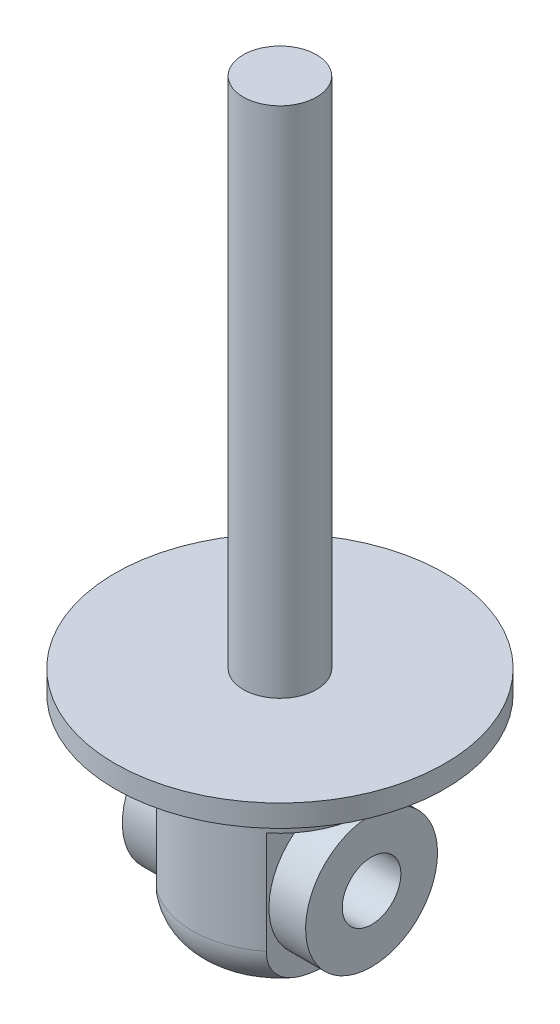
SolidWorks part; units mm, degrees
ref_plane "Plano frontal" through (0, 0, 0) normal (0, 0, 1) x (1, 0, 0)
ref_plane "Plano superior" through (0, 0, 0) normal (0, 1, 0) x (1, 0, 0)
ref_plane "Plano direito" through (0, 0, 0) normal (1, 0, 0) x (0, 0, -1)
sketch "Esboço1" plane through (0, 0, 0) normal (0, 1, 0) x (1, 0, 0)
  circle A0 centre (0, 0) radius 22.5
  dimension "D1" = 45
extrude "Ressalto-extrusão1" add sketch "Esboço1" along normal blind 3
sketch "Esboço2" plane through (0, 3, 0) normal (0, 1, 0) x (1, 0, 0)
  circle A0 centre (0, 0) radius 5
  dimension "D1" = 10
extrude "Ressalto-extrusão2" add sketch "Esboço2" along normal blind 70
sketch "Esboço3" plane through (0, 0, 0) normal (0, -1, 0) x (1, 0, 0)
  circle A0 centre (0, 0) radius 12
  dimension "D1" = 24
extrude "Ressalto-extrusão3" add sketch "Esboço3" along normal blind 28
fillet "Filete1" radius 6 1 edges at (0, -28, -12)
sketch "Esboço4" plane through (0, 0, 0) normal (0, 0, 1) x (1, 0, 0)
  line L0 (0, 0) -> (0, -28) construction
  line L1 (-6, -28) -> (6, -28) construction
  line L2 (7.5, -28) -> (30.7523, -28)
  line L3 (30.7523, -28) -> (30.7523, -8)
  line L4 (30.7523, -8) -> (7.5, -8)
  line L5 (7.5, -8) -> (7.5, -28)
  line L6 (-30.7523, -8) -> (-7.5, -8)
  line L7 (-30.7523, -28) -> (-30.7523, -8)
  line L8 (-7.5, -28) -> (-30.7523, -28)
  line L9 (-7.5, -8) -> (-7.5, -28)
  dimension "D1" = 15
  dimension "D2" = 20
extrude "Corte-extrusão1" cut sketch "Esboço4" against normal mid plane 28
sketch "Esboço5" plane through (7.5, 0, 0) normal (1, 0, 0) x (0, 0, -1)
  line L0 (0, 0) -> (0, -27.8095) construction
  line L1 (-12, 0) -> (12, 0) construction
  circle A0 centre (0, -17.0227) radius 4
  spline S0 degree 3 poles (-9.3675, -22) (-9.3675, -22.256) (-9.346, -22.5161) (-9.2617, -23.0236) (-9.1993, -23.2718) (-9.0353, -23.7573) (-8.9325, -23.9966) (-8.6933, -24.4529) (-8.5573, -24.67) (-8.2544, -25.0836) (-8.0864, -25.2813) (-7.7261, -25.6506) (-7.5349, -25.8216) (-6.9312, -26.2977) (-6.4844, -26.5672) (-5.5607, -27.0045) (-5.0803, -27.1758) (-4.0917, -27.4469) (-3.5846, -27.5457) (-2.5722, -27.6899) (-2.0636, -27.7363) (-1.0432, -27.7958) (-0.5315, -27.8091) (0.4943, -27.8098) (1.0101, -27.797) (2.0342, -27.7387) (2.5445, -27.6929) (3.56, -27.5501) (4.0672, -27.4524) (5.0646, -27.1812) (5.5488, -27.0094) (6.4792, -26.5703) (6.9277, -26.3001) (7.5323, -25.8239) (7.7237, -25.6529) (8.0841, -25.2839) (8.2538, -25.0844) (8.7096, -24.462) (8.9491, -24.0109) (9.1993, -23.2725) (9.2623, -23.0206) (9.3462, -22.5143) (9.3675, -22.2585) (9.3675, -22) knots 0 0 0 0 0.03125 0.03125 0.0625 0.0625 0.09375 0.09375 0.125 0.125 0.15625 0.15625 0.1875 0.1875 0.25 0.25 0.3125 0.3125 0.375 0.375 0.4375 0.4375 0.5 0.5 0.5625 0.5625 0.625 0.625 0.6875 0.6875 0.75 0.75 0.8125 0.8125 0.84375 0.84375 0.875 0.875 0.9375 0.9375 0.96875 0.96875 1 1 1 1 construction
  dimension "D1" = 8
extrude "Corte-extrusão3" cut sketch "Esboço5" against normal blind 28
sketch "Esboço7" plane through (0, 0, 0) normal (1, 0, 0) x (0, 0, -1)
  circle A0 centre (0, -17.0227) radius 9
  circle A1 centre (0, -17.0227) radius 4 construction
  circle A2 centre (0, -17.0227) radius 4
  dimension "D1" = 18
extrude "Ressalto-extrusão4" add sketch "Esboço7" along normal mid plane 25
